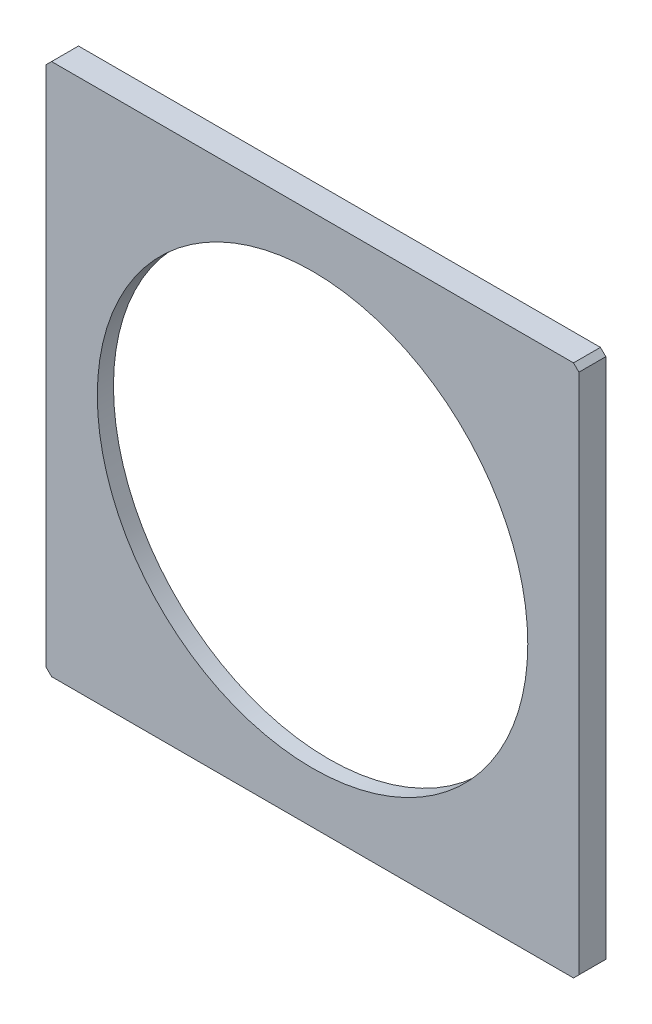
SolidWorks part; units mm, degrees
ref_plane "Front Plane" through (0, 0, 0) normal (1, 0, 0) x (0, 1, 0)
ref_plane "Top Plane" through (0, 0, 0) normal (0, 0, 1) x (0, 1, 0)
ref_plane "Right Plane" through (0, 0, 0) normal (0, 1, 0) x (-1, 0, 0)
sketch "Sketch1" plane through (0, 0, 0) normal (0, 0, 1) x (0, 1, 0)
  line L1 (49.5, -49.5) -> (-49.5, -49.5)
  line L2 (49.5, -49.5) -> (49.5, 49.5)
  line L3 (49.5, 49.5) -> (-49.5, 49.5)
  line L4 (-49.5, -49.5) -> (-49.5, 49.5)
  line L5 (49.5, -49.5) -> (-49.5, 49.5) construction
  line L6 (49.5, 49.5) -> (-49.5, -49.5) construction
  circle A0 centre (0, 0) radius 40
  point P0 (0, 0)
  dimension "D3" = 80
  dimension "D1" = 99
  dimension "D2" = 99
extrude "Boss-Extrude1" add sketch "Sketch1" along normal blind 5
sketch "Sketch2" plane through (0, 0, 0) normal (0, 0, -1) x (1, 0, 0)
  circle A0 centre (0, 0) radius 43
  circle A1 centre (0, 0) radius 40 construction
  dimension "D1" = 3
extrude "Cut-Extrude1" cut sketch "Sketch2" against normal blind 2 and the other way through all
chamfer "Chamfer1" distance 1 angle 45 4 edges at (-49.5, -49.5, 2.5) (-49.5, 49.5, 2.5) (49.5, 49.5, 2.5) (49.5, -49.5, 2.5)
